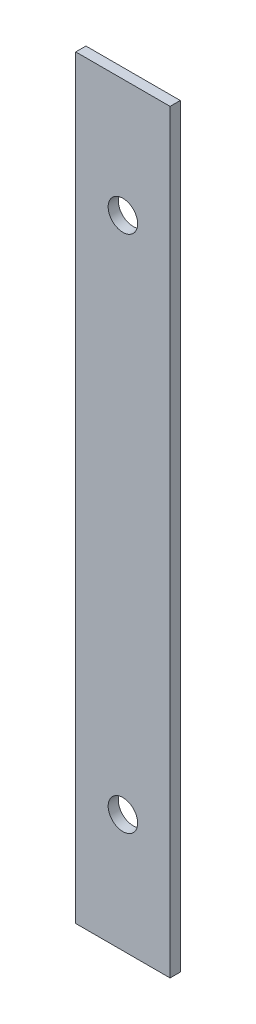
SolidWorks part; units mm, degrees
material "AISI 1020 Steel, Cold Rolled"
ref_plane "Front Plane" through (0, 0, 0) normal (0, 0, 1) x (1, 0, 0)
ref_plane "Top Plane" through (0, 0, 0) normal (0, 1, 0) x (1, 0, 0)
ref_plane "Right Plane" through (0, 0, 0) normal (1, 0, 0) x (0, 0, -1)
sketch "Sketch1" plane through (0, 0, 0) normal (0, 1, 0) x (1, 0, 0)
  line L1 (0, 0) -> (25.4, 0)
  line L2 (0, 0) -> (0, -2.7432)
  line L3 (0, -2.7432) -> (25.4, -2.7432)
  line L4 (25.4, 0) -> (25.4, -2.7432)
  dimension "D1" = 25.4
  dimension "D2" = 2.7432
extrude "Boss-Extrude1" add sketch "Sketch1" along normal blind 203.2
extrude "Cut-Extrude1" cut sketch "Sketch2" against normal through all and the other way through all
sketch "Sketch2" plane through (8.7917, 106.6067, 5.9182) normal (0, 0, 1) x (1, 0, 0)
  line L0 (360.1647, 83.8933) -> (360.1647, -93.9067) construction
  line L6 (347.4647, -5.0067) -> (371.2772, -5.0067) construction
  line L8 (3.9083, 83.8933) -> (3.9083, -93.9067) construction
  line L11 (-310.6722, 83.8933) -> (-310.6722, -93.9067) construction
  circle A0 centre (360.1647, 64.8433) radius 3.9688
  circle A1 centre (360.1647, -74.8567) radius 3.9688
  circle A3 centre (3.9083, 64.8433) radius 3.9687
  circle A4 centre (-310.6722, 64.8433) radius 3.9688
  circle A5 centre (3.9083, -74.8567) radius 3.9687
  circle A6 centre (-310.6722, -74.8567) radius 3.9688
